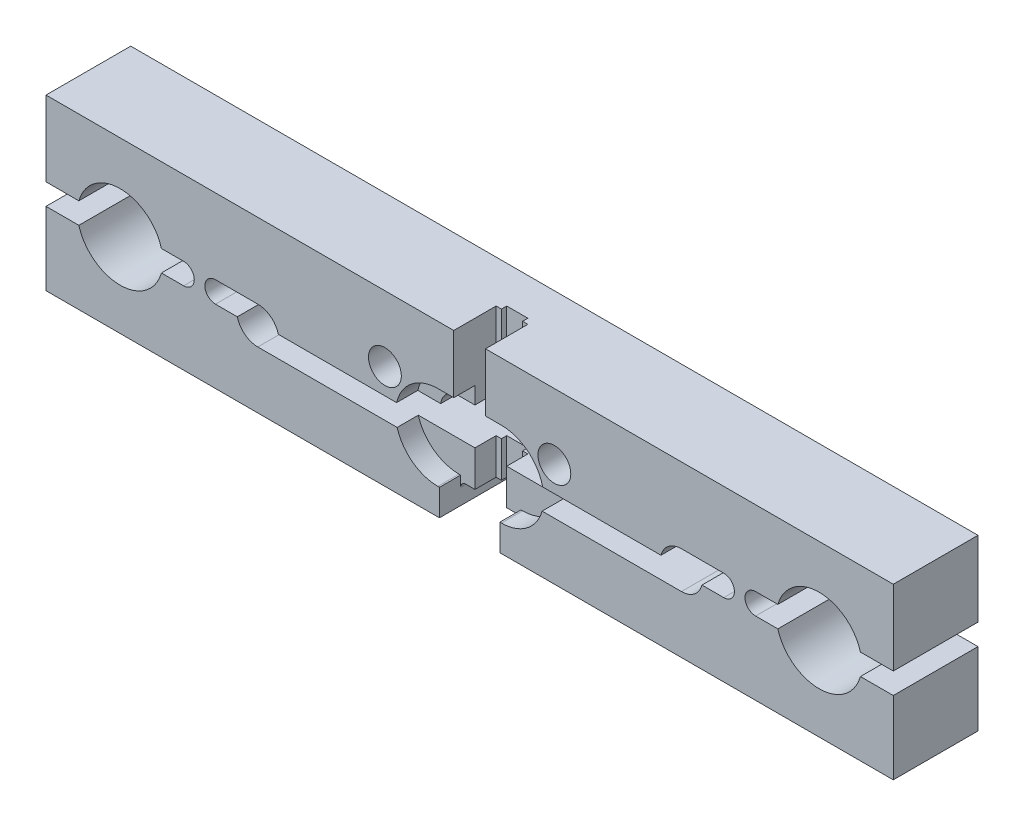
SolidWorks part; units mm, degrees
ref_plane "前视基准面" through (0, 0, 0) normal (0, 0, 1) x (1, 0, 0)
ref_plane "上视基准面" through (0, 0, 0) normal (0, 1, 0) x (1, 0, 0)
ref_plane "右视基准面" through (0, 0, 0) normal (1, 0, 0) x (0, 0, -1)
sketch "前视图草图" plane through (0, 0, 0) normal (0, 0, 1) x (1, 0, 0)
  line L0 (0, 0) -> (44.4821, 0) construction
  line L1 (0, 0) -> (0, 28.3185) construction
sketch "草图2" plane through (0, 0, 0) normal (0, 0, 1) x (1, 0, 0)
  line L0 (0, 0) -> (80, 0)
  line L1 (-200000, 0) -> (200044.4821, 0) construction
  line L2 (80, 0) -> (80, 16)
  line L3 (80, 16) -> (0, 16)
  line L4 (0, -200000) -> (0, 200028.3185) construction
  line L5 (0, 16) -> (0, 0)
  line L6 (7, 17.2957) -> (7, -8.7712) construction
  line L7 (73, 25.8617) -> (73, -10.6533) construction
  arc A0 (11.0488, 7.9) -> (2.9512, 7.9) centre (7, 7.8) ccw
  arc A2 (77.0488, 7.9) -> (68.9512, 7.9) centre (73, 7.8) ccw
  arc A3 (2.9512, 7.9) -> (11.0488, 7.9) centre (7, 8) ccw
  arc A4 (68.9512, 7.9) -> (77.0488, 7.9) centre (73, 8) ccw
  dimension "D3" = 7.8
  dimension "D5" = 8.1
  dimension "D9" = 8.1
  dimension "D10" = 8.1
  dimension "D11" = 8
  dimension "D12" = 8.1
  dimension "D1" = 16
  dimension "D2" = 80
  dimension "D4" = 7
  dimension "D7" = 7.8
  dimension "D14" = 8
  dimension "D21" = 7
extrude "凸台-拉伸1" add sketch "草图2" along normal blind 8
sketch "草图5" plane through (0, 0, 8) normal (0, 0, 1) x (1, 0, 0)
  line L0 (40, 9.8) -> (56.5376, 9.8) construction
  line L1 (0, -200000) -> (0, 200028.3185) construction
  line L2 (-200000, 0) -> (200044.4821, 0) construction
  circle A0 centre (40, 9.8) radius 8 construction
  circle A1 centre (48, 9.8) radius 1.55
  circle A2 centre (32, 9.8) radius 1.55
  dimension "D1" = 3.1
  dimension "D2" = 3.1
  dimension "D3" = 16
  dimension "D4" = 40
  dimension "D5" = 9.8
extrude "切除-拉伸3" cut sketch "草图5" against normal through all
sketch "草图6" plane through (0, 0, 8) normal (0, 0, 1) x (1, 0, 0)
  line L0 (-14.1885, 7.9) -> (-5.4375, 7.9) construction
  line L1 (-200000, 0) -> (200044.4821, 0) construction
  line L2 (0, 8.9) -> (0, 6.9)
  line L3 (0, -200000) -> (0, 200028.3185) construction
  line L4 (0, 6.9) -> (13, 6.9)
  line L5 (80, 0) -> (80, 16) construction
  line L6 (80, 6.9) -> (80, 8.9)
  line L7 (80, 8.9) -> (67, 8.9)
  line L10 (61.9365, 6.9) -> (64, 6.9)
  line L11 (20, 8.9) -> (16, 8.9)
  line L13 (20, 5.4) -> (60, 5.4)
  line L15 (58.0635, 7.4) -> (21.9365, 7.4)
  line L16 (20, 1015.1838) -> (20, 8.9) construction
  line L17 (60, 25.2492) -> (60, 8.9) construction
  line L18 (20, 5.4) -> (20, -1004.4799) construction
  line L20 (60, 5.4) -> (60, -19.6999) construction
  line L21 (16, 6.9) -> (18.0635, 6.9)
  line L25 (13, 8.9) -> (0, 8.9)
  line L26 (67, 6.9) -> (80, 6.9)
  line L27 (64, 8.9) -> (60, 8.9)
  arc A1 (20, 8.9) -> (22, 6.9) centre (20, 6.9) cw
  arc A2 (18, 7.4) -> (20, 5.4) centre (20, 7.4) ccw
  arc A3 (60, 5.4) -> (62, 7.4) centre (60, 7.4) ccw
  arc A4 (60, 8.9) -> (58, 6.9) centre (60, 6.9) ccw
  arc A5 (13, 6.9) -> (13, 8.9) centre (13, 7.9) ccw
  arc A6 (16, 8.9) -> (16, 6.9) centre (16, 7.9) ccw
  arc A7 (67, 8.9) -> (67, 6.9) centre (67, 7.9) ccw
  arc A8 (64, 6.9) -> (64, 8.9) centre (64, 7.9) ccw
  dimension "D5" = 13
  dimension "D1" = 7.9
  dimension "D2" = 2
  dimension "D3" = 1
  dimension "D4" = 20
  dimension "D6" = 2
  dimension "D7" = 0.5
  dimension "D8" = 16
  dimension "D9" = 20
  dimension "D10" = 13
  dimension "D11" = 16
extrude "切除-拉伸4" cut sketch "草图6" against normal through all
sketch "草图7" plane through (0, 0, 8) normal (0, 0, 1) x (1, 0, 0)
  line L0 (-200000, 0) -> (200044.4821, 0) construction
  line L1 (0, -200000) -> (0, 200028.3185) construction
  line L2 (80, 0) -> (80, 6.9) construction
  line L3 (77, -2) -> (74, -2)
  line L4 (77, 0) -> (74, 0)
  line L5 (6, 0) -> (3, 0)
  line L6 (6, -2) -> (3, -2)
  circle A0 centre (3, -1) radius 1
  circle A1 centre (6, -1) radius 1
  circle A2 centre (74, -1) radius 1
  circle A3 centre (77, -1) radius 1
  dimension "D1" = 2
  dimension "D2" = 2
  dimension "D3" = 2
  dimension "D4" = 2
  dimension "D5" = 3
  dimension "D6" = 6
  dimension "D7" = 3
  dimension "D8" = 6
sketch "草图8" plane through (0, 0, 8) normal (0, 0, 1) x (1, 0, 0)
  line L0 (38.5, 16) -> (41.5, 16)
  line L1 (80, 16) -> (0, 16) construction
  line L2 (41.5, 16) -> (41.5, 0)
  line L3 (-200000, 0) -> (200044.4821, 0) construction
  line L4 (41.5, 0) -> (38.5, 0)
  line L5 (38.5, 0) -> (38.5, 16)
  line L6 (0, -200000) -> (0, 200028.3185) construction
  dimension "D1" = 3
  dimension "D2" = 38.5
extrude "切除-拉伸5" cut sketch "草图8" against normal blind 4
sketch "草图9" plane through (0, 0, 8) normal (0, 0, 1) x (1, 0, 0)
  line L0 (37.15, 0) -> (42.85, 0)
  line L1 (-200000, 0) -> (200044.4821, 0) construction
  line L2 (42.85, 0) -> (42.85, 2)
  line L3 (42.85, 2) -> (37.15, 2)
  line L4 (37.15, 2) -> (37.15, 0)
  line L5 (0, -200000) -> (0, 200028.3185) construction
  circle A0 centre (37.65, 1.5) radius 0.5
  circle A1 centre (42.35, 1.5) radius 0.5
  point P4 (40, 0)
  line M17 (0, 0) -> (38.5, 0)
  line M18 (38.5, 0) -> (38.5, 5.4)
  dimension "D2" = 1
  dimension "D3" = 1
  dimension "D1" = 2
  dimension "D4" = 5.7
  dimension "D5" = 37.15
extrude "切除-拉伸6" cut sketch "草图9" against normal through all contours A0 | A1 | A1 L3 L0 L2 M18 | A0 L4 L3 M17 M18
sketch "草图10" plane through (0, 0, 8) normal (0, 0, 1) x (1, 0, 0)
  line L0 (-16.167, 6.5) -> (-7.3119, 6.5) construction
  line L1 (-200000, 0) -> (200044.4821, 0) construction
  line L2 (37, 25.4789) -> (37, 22.1592) construction
  line L3 (40, 28.0379) -> (40, 22.1592) construction
  line L4 (43, 28.0379) -> (43, 22.1592) construction
  line L5 (0, -200000) -> (0, 200028.3185) construction
  line L6 (80, 8.9) -> (80, 16) construction
  line L7 (37, 10.5) -> (43, 10.5)
  line L8 (43, 2.5) -> (37, 2.5)
  arc A0 (37, 10.5) -> (37, 2.5) centre (37, 6.5) ccw
  arc A1 (43, 2.5) -> (43, 10.5) centre (43, 6.5) ccw
  dimension "D5" = 8
  dimension "D6" = 8
  dimension "D1" = 6.5
  dimension "D2" = 40
  dimension "D3" = 37
  dimension "D4" = 37
extrude "切除-拉伸7" cut sketch "草图10" against normal blind 2
sketch "草图11" plane through (0, 0, 8) normal (0, 0, 1) x (1, 0, 0)
  line L0 (38.5, 5.4) -> (33.1542, 5.4) construction
  line L1 (46.8458, 5.4) -> (41.5, 5.4) construction
  line L2 (0, -200000) -> (0, 200028.3185) construction
  line L3 (80, 0) -> (80, 6.9) construction
  line L5 (37, 5.4) -> (43, 5.4)
  line L6 (37, 8.9) -> (43, 8.9)
  arc A0 (37, 8.9) -> (37, 5.4) centre (37, 7.15) ccw
  arc A1 (43, 5.4) -> (43, 8.9) centre (43, 7.15) ccw
  dimension "D1" = 3.5
  dimension "D2" = 3.5
  dimension "D3" = 37
  dimension "D4" = 37
extrude "切除-拉伸8" cut sketch "草图11" against normal through all
sketch "草图12" plane through (0, 0, 8) normal (0, 0, 1) x (1, 0, 0)
  line L0 (37.15, 0) -> (37.15, 2.5)
  line L1 (37, 2.5) -> (38.5, 2.5) construction
  line L2 (37.15, 2.5) -> (42.85, 2.5)
  line L3 (41.5, 2.5) -> (43, 2.5) construction
  line L4 (42.85, 2.5) -> (42.85, 0)
  line L5 (42.85, 0) -> (37.15, 0)
extrude "切除-拉伸9" cut sketch "草图12" against normal blind 2
sketch "草图13" plane through (0, 0, 4) normal (0, 0, 1) x (1, 0, 0)
  line L0 (40, 22.0777) -> (40, 18.5696) construction
  line L1 (0, -200000) -> (0, 200028.3185) construction
  line L2 (39, 16) -> (41, 16)
  line L3 (41.5, 16) -> (38.5, 16) construction
  line L4 (41, 16) -> (41, 2)
  line L5 (38.5, 2) -> (41.5, 2) construction
  line L6 (41, 2) -> (39, 2)
  line L7 (39, 2) -> (39, 16)
  dimension "D1" = 40
  dimension "D2" = 2
  dimension "D3" = 1
extrude "切除-拉伸10" cut sketch "草图13" against normal blind 0.5
